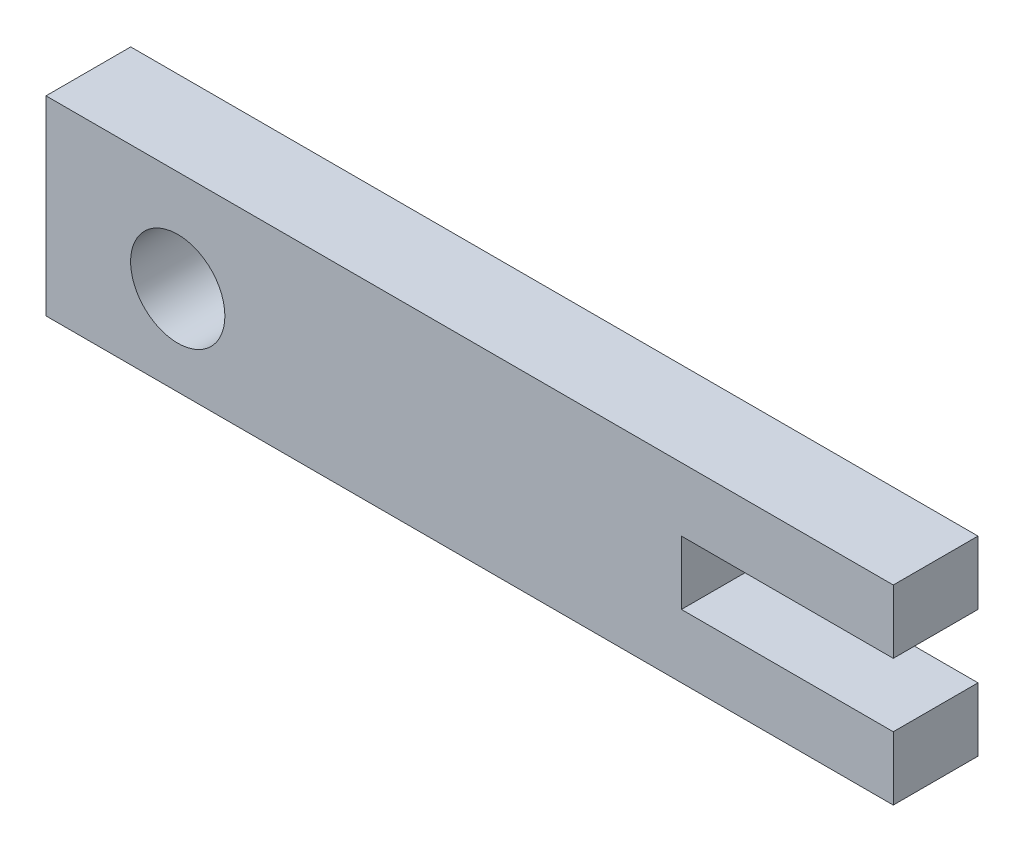
SolidWorks part; units mm, degrees
ref_plane "Alzado" through (0, 0, 0) normal (0, 0, 1) x (1, 0, 0)
ref_plane "Planta" through (0, 0, 0) normal (0, 1, 0) x (1, 0, 0)
ref_plane "Vista lateral" through (0, 0, 0) normal (1, 0, 0) x (0, 0, -1)
sketch "Croquis1" plane through (0, 0, 0) normal (0, 1, 0) x (1, 0, 0)
  line L1 (-175, -10) -> (175, -10)
  line L2 (-175, -10) -> (-175, 10)
  line L3 (-175, 10) -> (175, 10)
  line L4 (175, -10) -> (175, 10)
  line L5 (-175, -10) -> (175, 10) construction
  line L6 (-175, 10) -> (175, -10) construction
  point P0 (0, 0)
  dimension "D1" = 350
  dimension "D2" = 20
extrude "Saliente-Extruir1" add sketch "Croquis1" along normal blind 45
sketch "Croquis2" plane through (0, 0, -10) normal (0, 0, -1) x (-1, 0, 0)
  line L0 (-175, 0) -> (175, 0) construction
  line L1 (-165, 0) -> (-122.8, 0)
  line L2 (-165, 0) -> (-165, 42.2)
  line L3 (-165, 42.2) -> (-122.8, 42.2)
  line L4 (-122.8, 0) -> (-122.8, 42.2)
  line L5 (-175, 45) -> (-175, 0) construction
  line L6 (-165, 42.2) -> (-122.8, 0) construction
  circle A0 centre (-143.9, 21.1) radius 11.125
  dimension "D4" = 22.25
  dimension "D1" = 10
  dimension "D2" = 42.2
  dimension "D3" = 42.2
extrude "Cortar-Extruir1" cut sketch "Croquis2" against normal through all contours A0
mirror "Simetría1" about plane through (0, 0, 0) normal (1, 0, 0) of "Cortar-Extruir1"
sketch "Croquis3" plane through (0, 0, 10) normal (0, 0, 1) x (1, 0, 0)
  line L0 (0, 0) -> (25, 0)
  line L1 (-175, 0) -> (175, 0) construction
  line L2 (25, 0) -> (25, 15)
  line L3 (25, 15) -> (-25, 15)
  line L4 (-25, 15) -> (-25, 30)
  line L5 (-25, 30) -> (25, 30)
  line L6 (25, 30) -> (25, 45)
  line L7 (-175, 45) -> (175, 45) construction
  line L13 (-175, 0) -> (175, 0)
  line L14 (175, 0) -> (175, 45)
  line L15 (175, 45) -> (-175, 45)
  line L16 (-175, 45) -> (-175, 0)
  line L17 (-175, 0) -> (175, 0)
  line L18 (175, 0) -> (175, 45)
  line L19 (175, 45) -> (-175, 45)
  line L20 (-175, 45) -> (-175, 0)
  point P5 (-25, 22.5)
  circle M9 centre (143.9, 21.1) radius 11.125
  line M10 (-175, 0) -> (175, 0)
  line M11 (175, 0) -> (175, 45)
  line M12 (175, 45) -> (-175, 45)
  dimension "D1" = 15
  dimension "D2" = 15
  dimension "D3" = 25
  dimension "D4" = 50
  dimension "D5" = 50
  dimension "D6" = 0
extrude "Cortar-Extruir2" cut sketch "Croquis3" against normal through all contours L6 L5 L4 L3 L2 M10 M11 M12 M9
